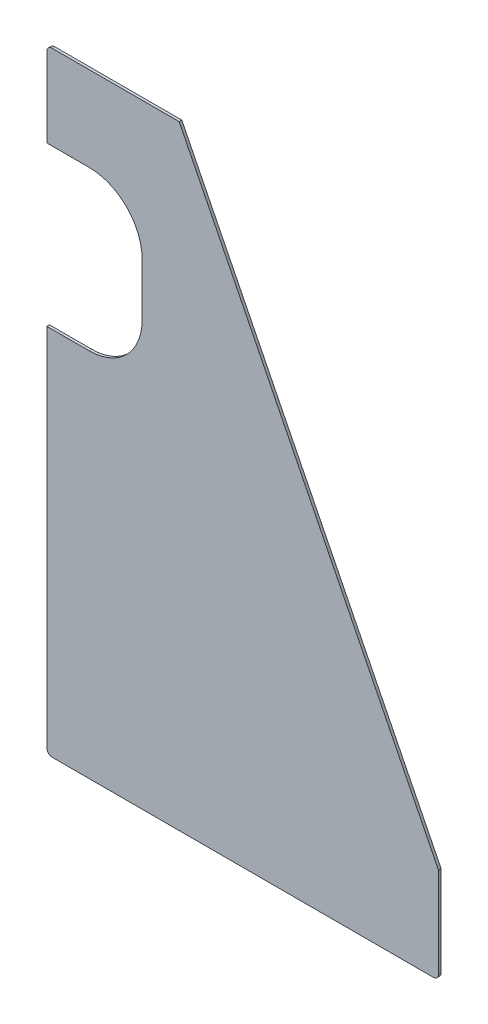
SolidWorks part; units mm, degrees
material "Thornel Mat VMA"
ref_plane "Front Plane" through (0, 0, 0) normal (0, 0, 1) x (1, 0, 0)
ref_plane "Top Plane" through (0, 0, 0) normal (0, 1, 0) x (1, 0, 0)
ref_plane "Right Plane" through (0, 0, 0) normal (1, 0, 0) x (0, 0, -1)
sketch "Sketch1" plane through (0, 0, 0) normal (0, 0, 1) x (1, 0, 0)
  line L1 (-370, -580) -> (370, -580)
  line L2 (-370, -580) -> (-370, 580)
  line L3 (-370, 580) -> (370, 580)
  line L4 (370, -580) -> (370, 580)
  line L5 (-370, -580) -> (370, 580) construction
  line L6 (-370, 580) -> (370, -580) construction
  point P0 (0, 0)
  dimension "D1" = 1160
  dimension "D2" = 740
extrude "Boss-Extrude1" add sketch "Sketch1" along normal blind 5
fillet "Fillet1" radius 10 4 edges at (-370, -580, 2.5) (370, -580, 2.5) (370, 580, 2.5) (-370, 580, 2.5)
sketch "Sketch2" plane through (0, 0, 0) normal (0, 0, -1) x (-1, 0, 0)
  line L0 (-370, -400) -> (120, 580)
  line L2 (-360, 580) -> (360, 580) construction
  line L3 (370, 570) -> (370, -570) construction
  line L4 (-370, -400) -> (-370, 580)
  line L5 (-370, 580) -> (120, 580)
  line L6 (360, -580) -> (-360, -580) construction
  line L7 (-370, -570) -> (-370, 570) construction
  point P9 (0, 0)
  dimension "D1" = 250
  dimension "D2" = 180
extrude "Cut-Extrude1" cut sketch "Sketch2" against normal through all
sketch "Sketch3" plane through (0, 0, 5) normal (0, 0, 1) x (1, 0, 0)
  line L0 (-370, 570) -> (-370, -570) construction
  line L1 (-550, 120) -> (-190, 120)
  line L2 (-550, 120) -> (-550, 420)
  line L3 (-550, 420) -> (-190, 420)
  line L4 (-190, 120) -> (-190, 420)
  line L5 (-550, 120) -> (-190, 420) construction
  line L6 (-550, 420) -> (-190, 120) construction
  line L8 (-360, -580) -> (360, -580) construction
  point P0 (-370, 270)
  point P7 (-270, 282.9403)
  dimension "D1" = 180
  dimension "D2" = 300
  dimension "D3" = 700
extrude "Cut-Extrude2" cut sketch "Sketch3" against normal through all
fillet "Fillet2" radius 100 2 edges at (-190, 120, 2.5) (-190, 420, 2.5)
